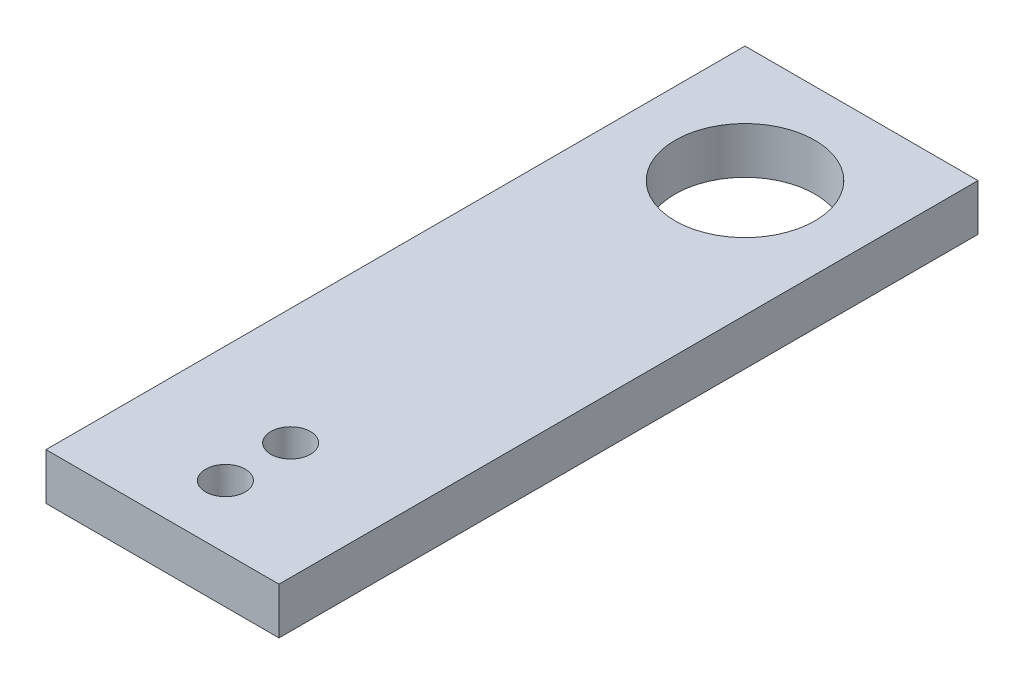
SolidWorks part; units mm, degrees
ref_plane "Front Plane" through (0, 0, 0) normal (0, 0, 1) x (1, 0, 0)
ref_plane "Top Plane" through (0, 0, 0) normal (0, 1, 0) x (1, 0, 0)
ref_plane "Right Plane" through (0, 0, 0) normal (1, 0, 0) x (0, 0, -1)
sketch "Sketch1" plane through (0, 0, 0) normal (0, 1, 0) x (1, 0, 0)
  line L0 (0, 0) -> (0, 25) construction
  line L1 (25, 25) -> (-25, 25)
  line L4 (-25, 25) -> (-25, -125)
  line L5 (-25, -125) -> (25, -125)
  line L6 (25, 25) -> (25, -125)
  circle A0 centre (0, 0) radius 15
  point P7 (0, 25)
  dimension "D1" = 25
  dimension "D2" = 30
  dimension "D3" = 50
  dimension "D4" = 150
extrude "Boss-Extrude1" add sketch "Sketch1" along normal blind 10
sketch "Sketch2" plane through (0, 0, 0) normal (0, 1, 0) x (1, 0, 0)
  line L0 (0, -125) -> (0, -111.5) construction
  line L1 (-25, -125) -> (25, -125) construction
  line L2 (0, -111.5) -> (0, -97.5) construction
  circle A0 centre (0, -111.5) radius 4.25
  circle A1 centre (0, -97.5) radius 4.25
  point P8 (0, -113.3791)
  dimension "D1" = 8.5
  dimension "D2" = 8.5
  dimension "D3" = 14
  dimension "D4" = 13.5
extrude "Cut-Extrude1" cut sketch "Sketch2" along normal blind 10
